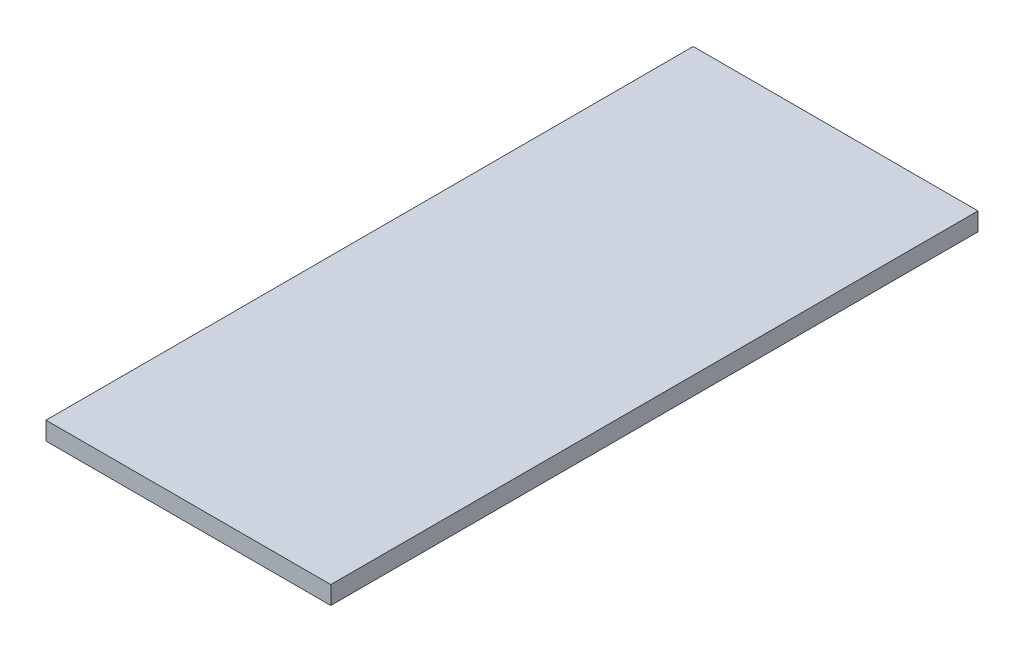
SolidWorks part; units mm, degrees
ref_plane "Front Plane" through (0, 0, 0) normal (0, 0, 1) x (1, 0, 0)
ref_plane "Top Plane" through (0, 0, 0) normal (0, 1, 0) x (1, 0, 0)
ref_plane "Right Plane" through (0, 0, 0) normal (1, 0, 0) x (0, 0, -1)
sketch "Sketch1" plane through (0, 0, 0) normal (0, 1, 0) x (1, 0, 0)
  line L1 (-55, -125) -> (55, -125)
  line L2 (-55, -125) -> (-55, 125)
  line L3 (-55, 125) -> (55, 125)
  line L4 (55, -125) -> (55, 125)
extrude "Boss-Extrude1" add sketch "Sketch1" along normal blind 7
